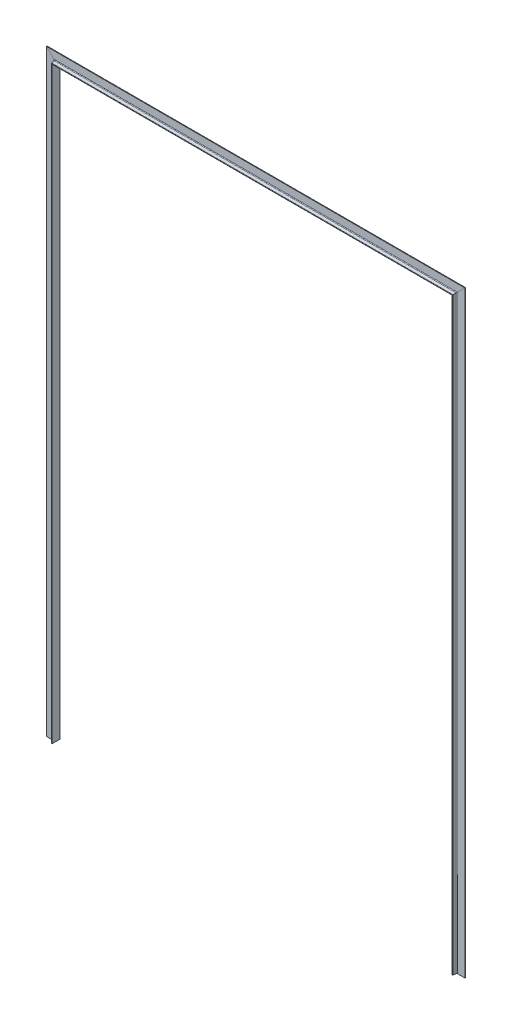
SolidWorks part; units mm, degrees
material "ASTM A36 Steel"
ref_plane "Front Plane" through (0, 0, 0) normal (0, 0, 1) x (1, 0, 0)
ref_plane "Top Plane" through (0, 0, 0) normal (0, 1, 0) x (1, 0, 0)
ref_plane "Right Plane" through (0, 0, 0) normal (1, 0, 0) x (0, 0, -1)
sketch "Sketch1" plane through (0, 0, 0) normal (0, 0, 1) x (1, 0, 0)
  line L0 (0, 0) -> (0, 10000)
  line L1 (0, 10000) -> (7000, 10000)
  line L2 (7000, 10000) -> (7000, 0)
  dimension "D1" = 10000
  dimension "D2" = 7000
other "St section ST6X17.5(2)"
ref_plane "Plane2" through (0, 0, 0) normal (0, 1, 0) x (0, 0, 1)
sketch "Sketch12" plane through (0, 0, 0) normal (0, 1, 0) x (0, 0, 1)
  line L0 (-64.4906, 152.4) -> (64.4906, 152.4)
  line L2 (-5.4356, 0) -> (-5.4356, 123.952)
  line L3 (-14.9864, 135.2265) -> (-60.0336, 142.7349)
  line L5 (-64.4906, 152.4) -> (-64.4906, 147.9963)
  line L6 (64.4906, 152.4) -> (64.4906, 147.9963)
  line L7 (60.0336, 142.7349) -> (14.9864, 135.2265)
  line L8 (5.4356, 123.952) -> (5.4356, 0)
  line L9 (64.4906, 138.557) -> (-64.4906, 138.557) construction
  line L12 (-5.4356, 0) -> (5.4356, 0)
  arc A0 (-60.0336, 142.7349) -> (-64.4906, 147.9963) centre (-59.1566, 147.9963) cw
  arc A1 (-5.4356, 123.952) -> (-14.9864, 135.2265) centre (-16.8656, 123.952) ccw
  arc A2 (14.9864, 135.2265) -> (5.4356, 123.952) centre (16.8656, 123.952) ccw
  arc A3 (60.0336, 142.7349) -> (64.4906, 147.9963) centre (59.1566, 147.9963) ccw
  point P9 (0, 152.4)
  point P18 (0, 33.9014)
  point P20 (-5.4356, 61.976)
  point P22 (5.4356, 61.976)
  point P23 (0, 0)
  point P24 (0, 0)
  dimension "RI" = 11.43
  dimension "D2" = 9.463
  dimension "RA" = 5.334
  dimension "D1" = 123.952
  dimension "TW" = 10.8712
  dimension "BF" = 128.9812
  dimension "DEPTH" = 152.4
  dimension "TF" = 13.843
  dimension "delta" = 59.055
